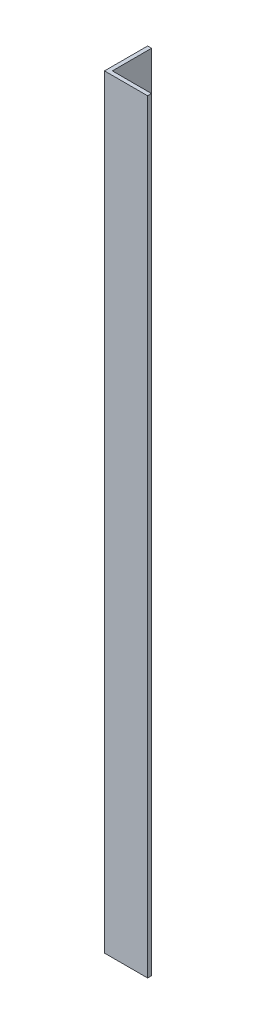
SolidWorks part; units mm, degrees
ref_plane "Спереди" through (0, 0, 0) normal (0, 0, 1) x (1, 0, 0)
ref_plane "Сверху" through (0, 0, 0) normal (0, 1, 0) x (1, 0, 0)
ref_plane "Справа" through (0, 0, 0) normal (1, 0, 0) x (0, 0, -1)
sketch "Эскиз1" plane through (0, 0, 0) normal (0, 1, 0) x (1, 0, 0)
  line L0 (0, -1.0719) -> (0, -21.0719)
  line L1 (0, -21.0719) -> (20, -21.0719)
  line L2 (20, -21.0719) -> (20, -23.0719)
  line L3 (20, -23.0719) -> (-2, -23.0719)
  line L4 (-2, -23.0719) -> (-2, -1.0719)
  line L5 (-2, -1.0719) -> (0, -1.0719)
extrude "Вытянуть1" add sketch "Эскиз1" along normal blind 390
